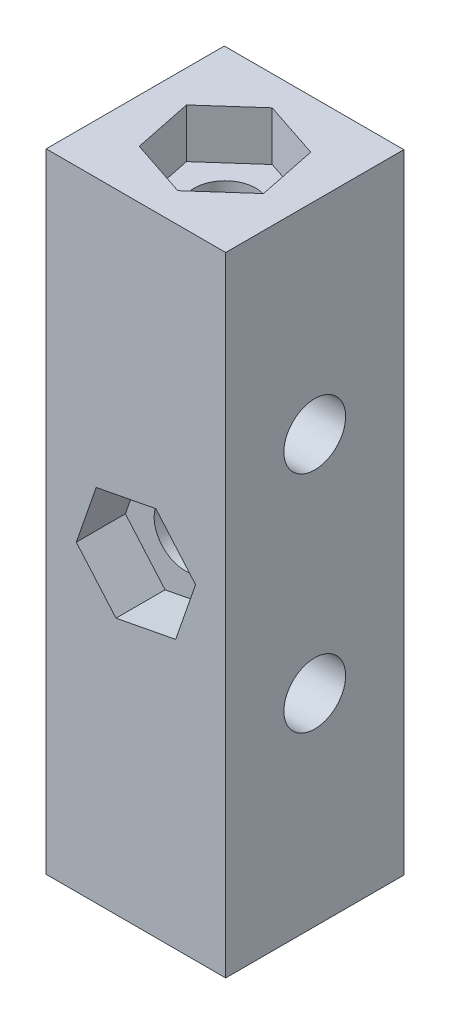
SolidWorks part; units mm, degrees
ref_plane "前基準面" through (0, 0, 0) normal (0, 0, 1) x (1, 0, 0)
ref_plane "上基準面" through (0, 0, 0) normal (0, 1, 0) x (1, 0, 0)
ref_plane "右基準面" through (0, 0, 0) normal (1, 0, 0) x (0, 0, -1)
sketch "草圖1" plane through (0, 0, 0) normal (0, 0, 1) x (1, 0, 0)
  line L1 (7.074, 18.1659) -> (19.874, 18.1659)
  line L2 (7.074, 18.1659) -> (7.074, -26.6341)
  line L3 (7.074, -26.6341) -> (19.874, -26.6341)
  line L4 (19.874, 18.1659) -> (19.874, -26.6341)
  dimension "D1" = 44.8
  dimension "D2" = 12.8
extrude "填料-伸長1" add sketch "草圖1" along normal blind 12.7
sketch "草圖2" plane through (0, 0, 12.7) normal (0, 0, 1) x (1, 0, 0)
  line L0 (7.074, 18.1659) -> (7.074, -26.6341) construction
  line L1 (19.874, 18.1659) -> (7.074, 18.1659) construction
  circle A0 centre (13.474, -4.2341) radius 2.2
  dimension "D1" = 4.4
  dimension "D2" = 6.4
  dimension "D3" = 22.4
extrude "除料-伸長1" cut sketch "草圖2" against normal through all
sketch "草圖3" plane through (7.074, 0, 0) normal (-1, 0, 0) x (0, 0, 1)
  line L0 (12.7, 18.1659) -> (0, 18.1659) construction
  line L1 (0, 18.1659) -> (0, -26.6341) construction
  circle A0 centre (6.35, 3.7659) radius 2.2
  circle A1 centre (6.35, -12.2341) radius 2.2
  dimension "D1" = 4.4
  dimension "D2" = 14.4
  dimension "D3" = 6.35
  dimension "D4" = 2
extrude "除料-伸長2" cut sketch "草圖3" against normal through all
sketch "草圖4" plane through (0, 18.1659, 0) normal (0, 1, 0) x (1, 0, 0)
  line L1 (7.074, -12.7) -> (7.074, 0) construction
  line L2 (19.874, -12.7) -> (7.074, -12.7) construction
  circle A0 centre (13.474, -6.35) radius 2.2
  dimension "D1" = 6.4
  dimension "D2" = 6.35
  dimension "D3" = 4.4
extrude "除料-伸長3" cut sketch "草圖4" against normal through all
sketch "草圖5" plane through (0, 0, 12.7) normal (0, 0, 1) x (1, 0, 0)
  line L1 (9.2212, -5.0488) -> (12.0531, -8.3245)
  line L2 (12.0531, -8.3245) -> (16.3059, -7.5099)
  line L3 (16.3059, -7.5099) -> (17.7268, -3.4195)
  line L4 (17.7268, -3.4195) -> (14.8949, -0.1438)
  line L5 (14.8949, -0.1438) -> (10.6421, -0.9584)
  line L6 (10.6421, -0.9584) -> (9.2212, -5.0488)
  circle A0 centre (13.474, -4.2341) radius 3.75 construction
extrude "除料-伸長4" cut sketch "草圖5" against normal blind 3.5
sketch "草圖6" plane through (7.074, 0, 0) normal (-1, 0, 0) x (0, 0, 1)
  line L0 (9.7403, -14.9279) -> (10.378, -10.645)
  line L1 (9.7403, 1.0721) -> (10.378, 5.355)
  line L2 (10.378, 5.355) -> (6.9877, 8.0488)
  line L3 (6.9877, 8.0488) -> (2.9597, 6.4596)
  line L4 (2.9597, 6.4596) -> (2.322, 2.1767)
  line L5 (2.322, 2.1767) -> (5.7123, -0.5171)
  line L6 (5.7123, -0.5171) -> (9.7403, 1.0721)
  line L7 (10.378, -10.645) -> (6.9877, -7.9512)
  line L8 (6.9877, -7.9512) -> (2.9597, -9.5404)
  line L9 (2.9597, -9.5404) -> (2.322, -13.8233)
  line L10 (2.322, -13.8233) -> (5.7123, -16.5171)
  line L11 (5.7123, -16.5171) -> (9.7403, -14.9279)
  circle A0 centre (6.35, 3.7659) radius 3.75 construction
  dimension "D1" = 2
extrude "除料-伸長5" cut sketch "草圖6" against normal blind 3.5
sketch "草圖7" plane through (0, -26.6341, 0) normal (0, -1, 0) x (1, 0, 0)
  line L1 (17.4079, 4.5406) -> (17.008, 8.8522)
  line L2 (17.008, 8.8522) -> (13.0741, 10.6616)
  line L3 (13.0741, 10.6616) -> (9.5401, 8.1594)
  line L4 (9.5401, 8.1594) -> (9.94, 3.8478)
  line L5 (9.94, 3.8478) -> (13.8739, 2.0384)
  line L6 (13.8739, 2.0384) -> (17.4079, 4.5406)
  circle A0 centre (13.474, 6.35) radius 3.75 construction
  dimension "D1" = 7.5
extrude "除料-伸長6" cut sketch "草圖7" against normal blind 3.5
sketch "草圖8" plane through (0, 18.1659, 0) normal (0, 1, 0) x (1, 0, 0)
  line L1 (14.3481, -10.591) -> (17.5838, -7.7136)
  line L2 (17.5838, -7.7136) -> (16.7098, -3.4726)
  line L3 (16.7098, -3.4726) -> (12.6, -2.109)
  line L4 (12.6, -2.109) -> (9.3642, -4.9864)
  line L5 (9.3642, -4.9864) -> (10.2382, -9.2274)
  line L6 (10.2382, -9.2274) -> (14.3481, -10.591)
  circle A0 centre (13.474, -6.35) radius 3.75 construction
  dimension "D1" = 7.5
extrude "除料-伸長7" cut sketch "草圖8" against normal blind 3.5
